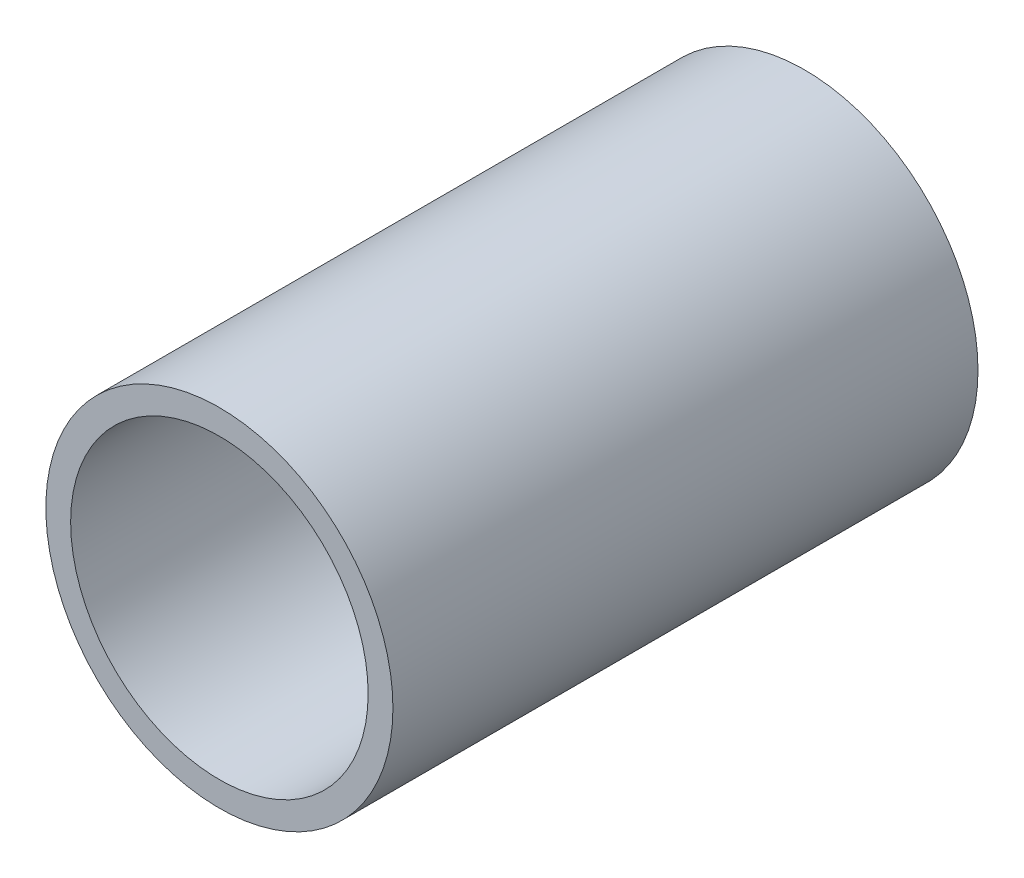
SolidWorks part; units mm, degrees
material "Acrylic (Medium-high impact)"
ref_plane "Front Plane" through (0, 0, 0) normal (0, 0, 1) x (1, 0, 0)
ref_plane "Top Plane" through (0, 0, 0) normal (0, 1, 0) x (1, 0, 0)
ref_plane "Right Plane" through (0, 0, 0) normal (1, 0, 0) x (0, 0, -1)
sketch "Sketch1" plane through (0, 0, 0) normal (0, 0, 1) x (1, 0, 0)
  circle A0 centre (0, 0) radius 38.1
  circle A1 centre (0, 0) radius 44.45
  dimension "D1" = 88.9
  dimension "D2" = 76.2
extrude "Boss-Extrude1" add sketch "Sketch1" along normal mid plane 149.86
